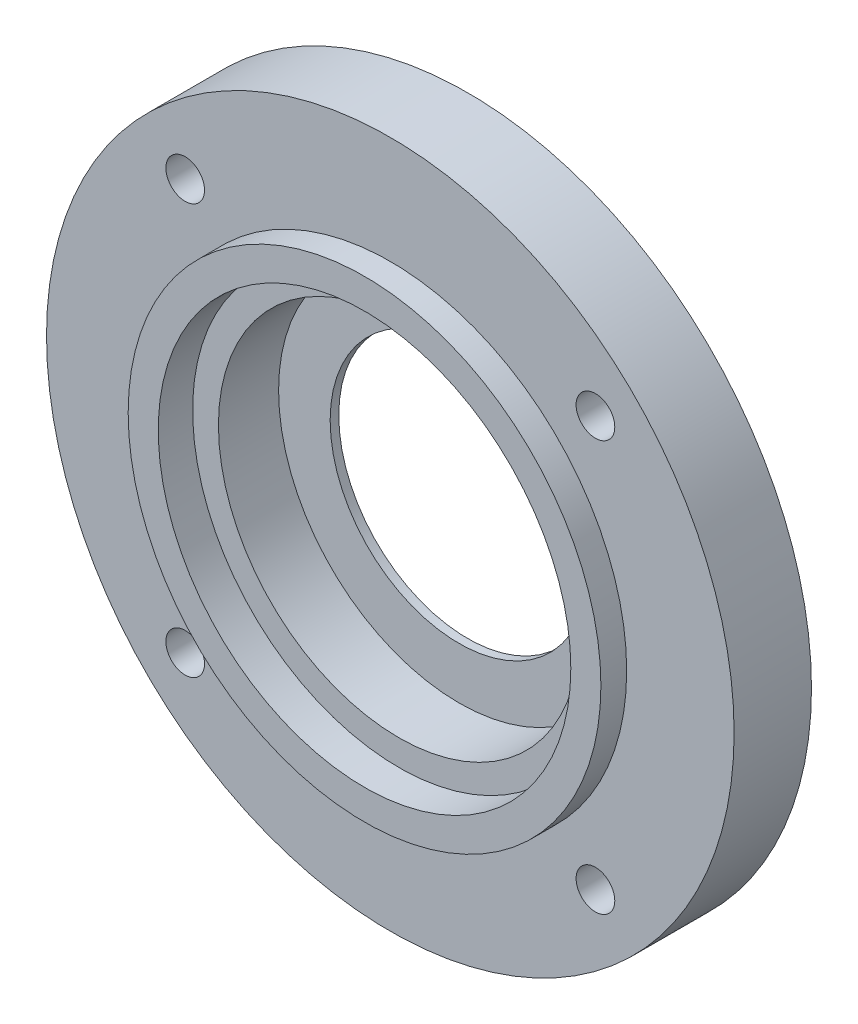
SolidWorks part; units mm, degrees
material "1.0503 (C45)"
ref_plane "Front Plane" through (0, 0, 0) normal (0, 0, 1) x (1, 0, 0)
ref_plane "Top Plane" through (0, 0, 0) normal (0, 1, 0) x (1, 0, 0)
ref_plane "Right Plane" through (0, 0, 0) normal (1, 0, 0) x (0, 0, -1)
sketch "Sketch3" plane through (0, 0, 0) normal (0, 1, 0) x (1, 0, 0)
  line L0 (15, 105) -> (40, 105)
  line L1 (40, 105) -> (40, 96)
  line L2 (40, 96) -> (27.5, 96)
  line L3 (27.5, 96) -> (27.5, 93)
  line L4 (27.5, 93) -> (24, 93)
  line L5 (24, 93) -> (24, 97)
  line L6 (24, 97) -> (21, 97)
  line L7 (21, 97) -> (21, 104)
  line L8 (21, 104) -> (15, 104)
  line L9 (15, 104) -> (15, 105)
  line L10 (0, -150) -> (0, 150) construction
revolve "REV_Seal_Cover_28x42x7" add sketch "Sketch3" angle 360 about L10
sketch "Sketch4" plane through (0, 0, 0) normal (0, 0, 1) x (1, 0, 0)
  circle A0 centre (23.8649, 23.8649) radius 2.25
  circle A1 centre (-23.8649, 23.8649) radius 2.25
  circle A2 centre (-23.8649, -23.8649) radius 2.25
  circle A3 centre (23.8649, -23.8649) radius 2.25
extrude "CUT_4xD4.5_PCD67.5" cut sketch "Sketch4" along normal mid plane 300
